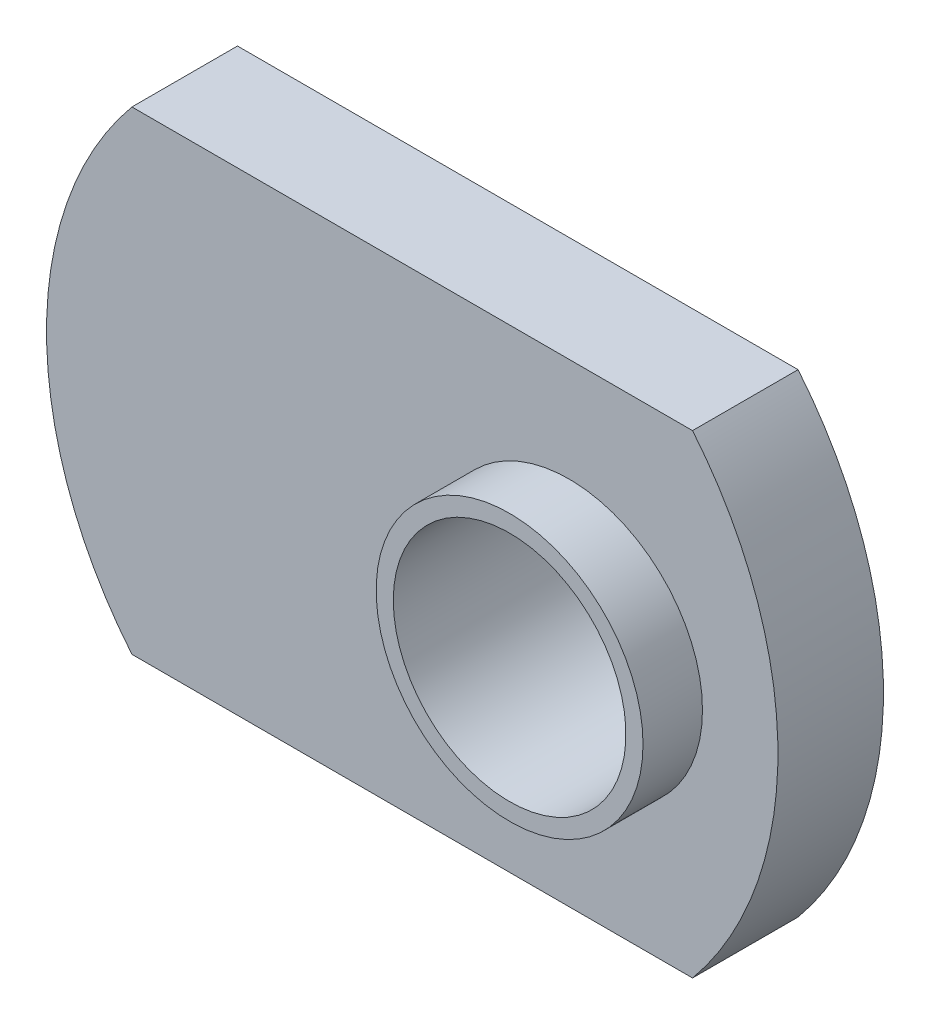
SolidWorks part; units mm, degrees
material "AISI 1020"
ref_plane "Front Plane" through (0, 0, 0) normal (0, 0, 1) x (1, 0, 0)
ref_plane "Top Plane" through (0, 0, 0) normal (0, 1, 0) x (1, 0, 0)
ref_plane "Right Plane" through (0, 0, 0) normal (1, 0, 0) x (0, 0, -1)
sketch "Sketch1" plane through (0, 0, 0) normal (0, 0, 1) x (1, 0, 0)
  line L88 (102.3414, 136.5714) -> (121.4981, 136.5714)
  line L89 (102.3414, 120.3713) -> (121.4981, 120.3713)
  arc A3 (102.3414, 136.5714) -> (102.3414, 120.3713) centre (112.123, 128.4713) ccw
  arc A4 (121.4981, 120.3713) -> (121.4981, 136.5714) centre (111.7166, 128.4713) ccw
extrude "Extrude1" add sketch "Sketch1" along normal blind 3.6068
sketch "Sketch4" plane through (0, 0, 3.6068) normal (0, 0, 1) x (1, 0, 0)
  line L0 (99.4263, 128.7646) -> (124.4132, 128.7646) construction
  circle A0 centre (117.2792, 128.4713) radius 4.5593
  arc A1 (102.3414, 136.5714) -> (102.3414, 120.3713) centre (112.123, 128.4713) ccw construction
  arc A2 (121.4981, 120.3713) -> (121.4981, 136.5714) centre (111.7166, 128.4713) ccw construction
  dimension "D1" = 9.1186
  dimension "D2" = 7.134
extrude "Extrude3" add sketch "Sketch4" along normal blind 2.032
sketch "Sketch6" plane through (0, 0, 0) normal (0, 0, -1) x (-1, 0, 0)
  circle A0 centre (-117.2792, 128.4713) radius 3.9751
  dimension "D1" = 7.9502
extrude "Cut-Extrude1" cut sketch "Sketch6" against normal through all
